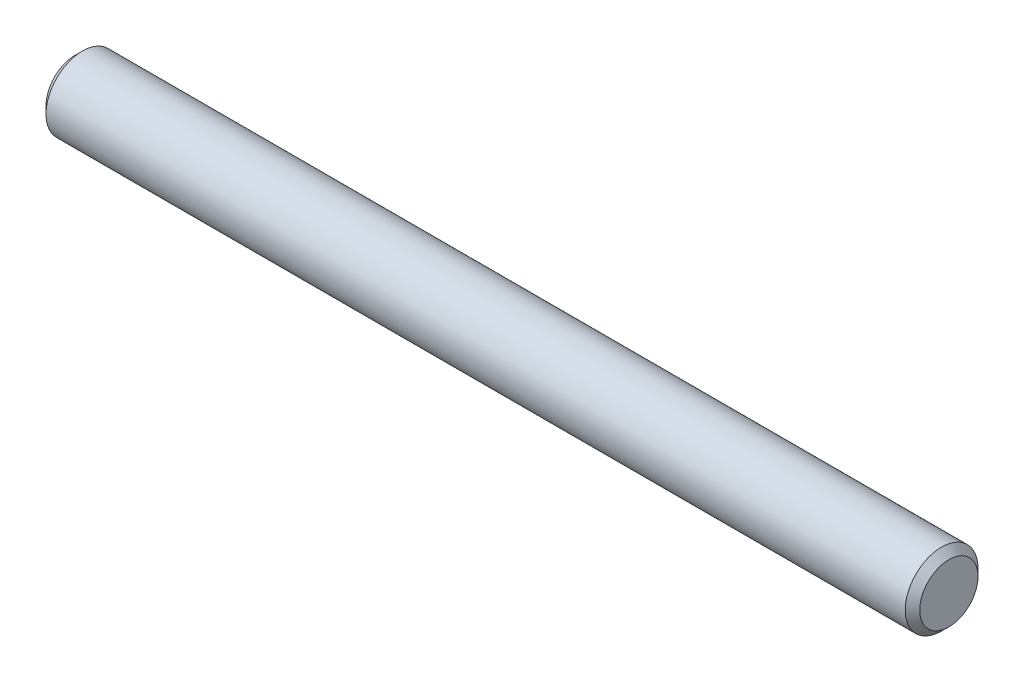
SolidWorks part; units mm, degrees
ref_plane "Front" through (0, 0, 0) normal (0, 0, 1) x (1, 0, 0)
ref_plane "Top" through (0, 0, 0) normal (0, 1, 0) x (1, 0, 0)
ref_plane "Right" through (0, 0, 0) normal (1, 0, 0) x (0, 0, -1)
sketch "Sketch1" plane through (0, 0, 0) normal (0, 0, 1) x (1, 0, 0)
  line L0 (-38.1, 0) -> (38.1, 0) construction
  line L1 (38.1, 3.175) -> (38.1, -3.175) construction
  line L2 (-38.1, 3.175) -> (-38.1, -3.175) construction
  dimension "Length" = 76.2
  dimension "Diameter" = 6.35
sketch "Sketch2" plane through (0, 0, 0) normal (1, 0, 0) x (0, 0, -1)
  circle A0 centre (0, 0) radius 3.175
extrude "Extrude1" add sketch "Sketch2" against normal up to vertex (38.1 mm away) and the other way up to vertex (38.1 mm away) up to point (-38.1, 3.175, 0) other way up to point (38.1, 3.175, 0)
chamfer "Chamfer1" distance 0.635 angle 45 2 edges at (38.1, 0, -3.175) (-38.1, 0, -3.175)
equation "\"D1@Chamfer1\" = \"Diameter@Sketch1\"*.1"
